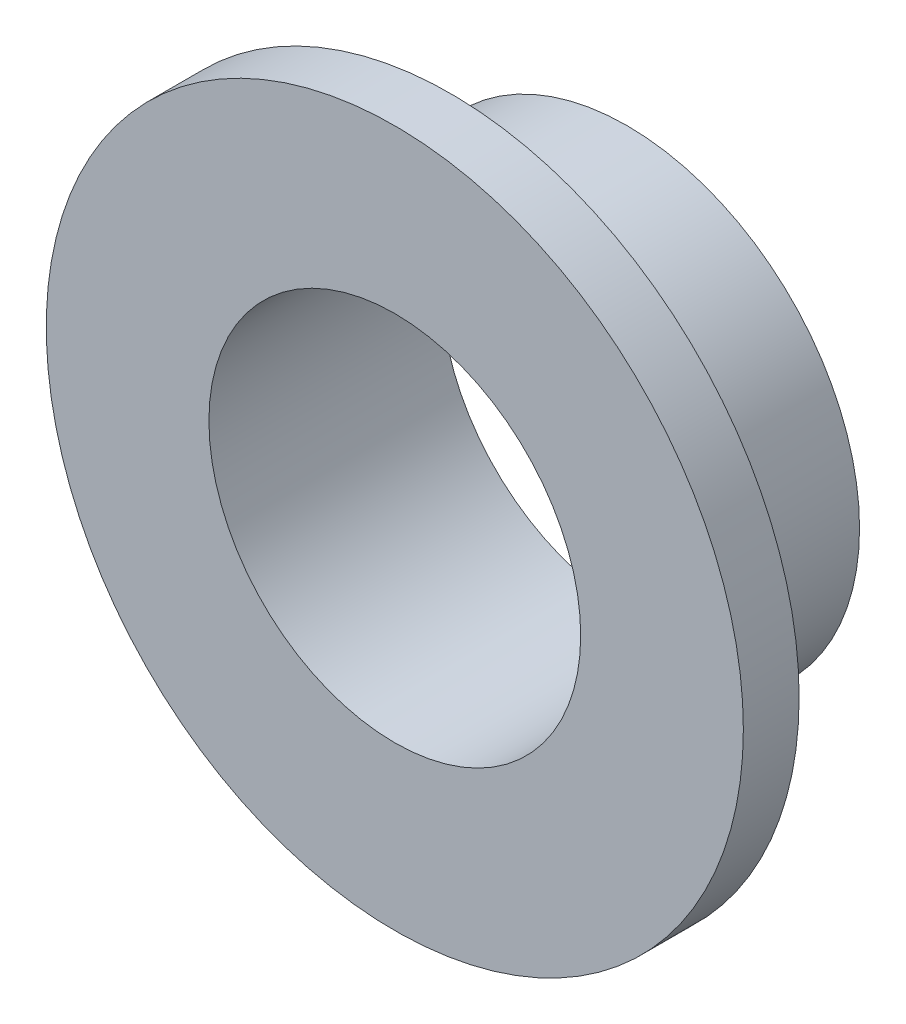
SolidWorks part; units mm, degrees
ref_plane "Front Plane" through (0, 0, 0) normal (0, 0, 1) x (1, 0, 0)
ref_plane "Top Plane" through (0, 0, 0) normal (0, 1, 0) x (1, 0, 0)
ref_plane "Right Plane" through (0, 0, 0) normal (1, 0, 0) x (0, 0, -1)
sketch "Sketch1" plane through (0, 0, 0) normal (1, 0, 0) x (0, 0, -1)
  line L0 (0, 4) -> (0, 7.5)
  line L1 (0, 7.5) -> (1.2, 7.5)
  line L2 (1.2, 7.5) -> (1.2, 5)
  line L3 (1.2, 5) -> (5, 5)
  line L4 (5, 5) -> (5, 4)
  line L5 (5, 4) -> (0, 4)
  line L6 (0, 0) -> (17.5023, 0) construction
  dimension "D1" = 4
  dimension "D2" = 5
  dimension "D3" = 7.5
  dimension "D4" = 1.2
  dimension "D5" = 5
revolve "Revolve1" add sketch "Sketch1" angle 360 about L6
